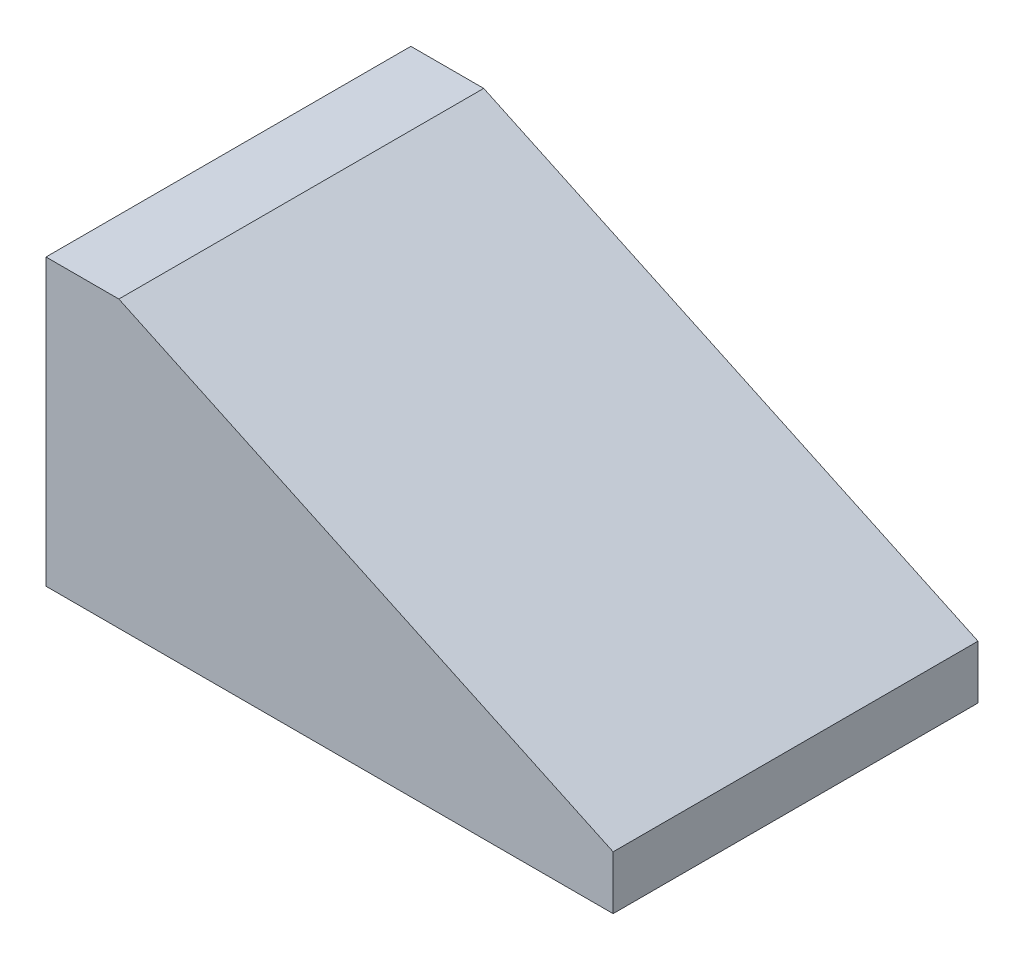
SolidWorks part; units mm, degrees
ref_plane "Front Plane" through (0, 0, 0) normal (0, 0, 1) x (1, 0, 0)
ref_plane "Top Plane" through (0, 0, 0) normal (0, 1, 0) x (1, 0, 0)
ref_plane "Right Plane" through (0, 0, 0) normal (1, 0, 0) x (0, 0, -1)
sketch "Sketch1" plane through (0, 0, 0) normal (0, 0, 1) x (1, 0, 0)
  line L0 (0, 43.8713) -> (0, 0)
  line L1 (0, 0) -> (87.2509, 0)
  line L2 (87.2509, 0) -> (87.2509, 8.2425)
  line L3 (87.2509, 8.2425) -> (11.2073, 43.8713)
  line L4 (11.2073, 43.8713) -> (0, 43.8713)
extrude "Extrude1" add sketch "Sketch1" against normal blind 56.134
